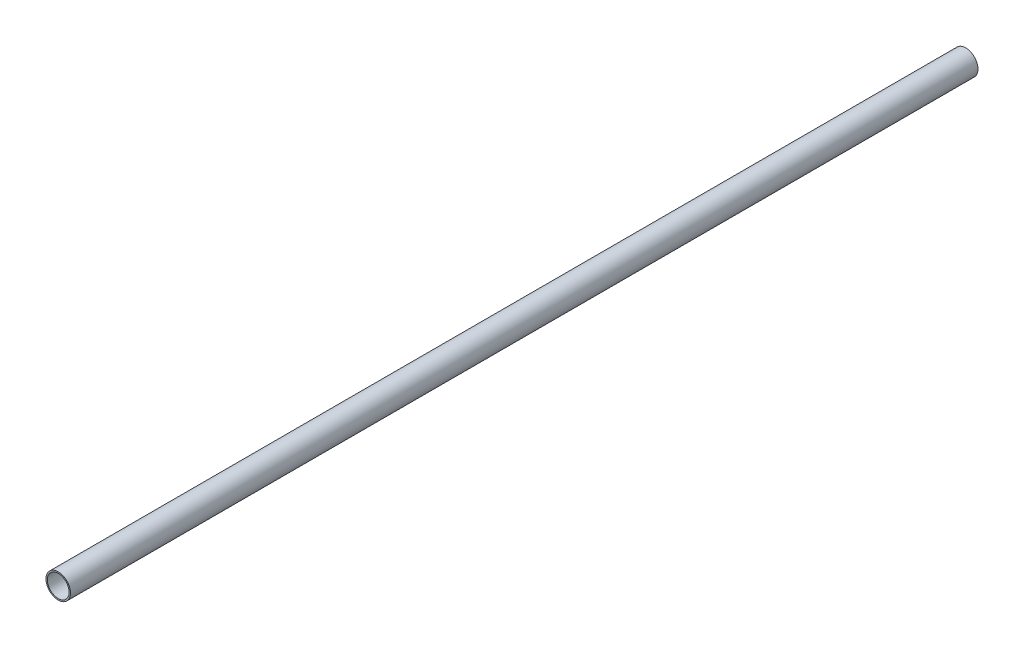
SolidWorks part; units mm, degrees
ref_plane "Front Plane" through (0, 0, 0) normal (0, 0, 1) x (1, 0, 0)
ref_plane "Top Plane" through (0, 0, 0) normal (0, 1, 0) x (1, 0, 0)
ref_plane "Right Plane" through (0, 0, 0) normal (1, 0, 0) x (0, 0, -1)
sketch "Sketch1" plane through (0, 0, 0) normal (0, 0, 1) x (1, 0, 0)
  circle A0 centre (0, 0) radius 12
  circle A1 centre (0, 0) radius 13.5
  dimension "D1" = 27
  dimension "D2" = 24
extrude "Boss-Extrude1" add sketch "Sketch1" along normal blind 1000
